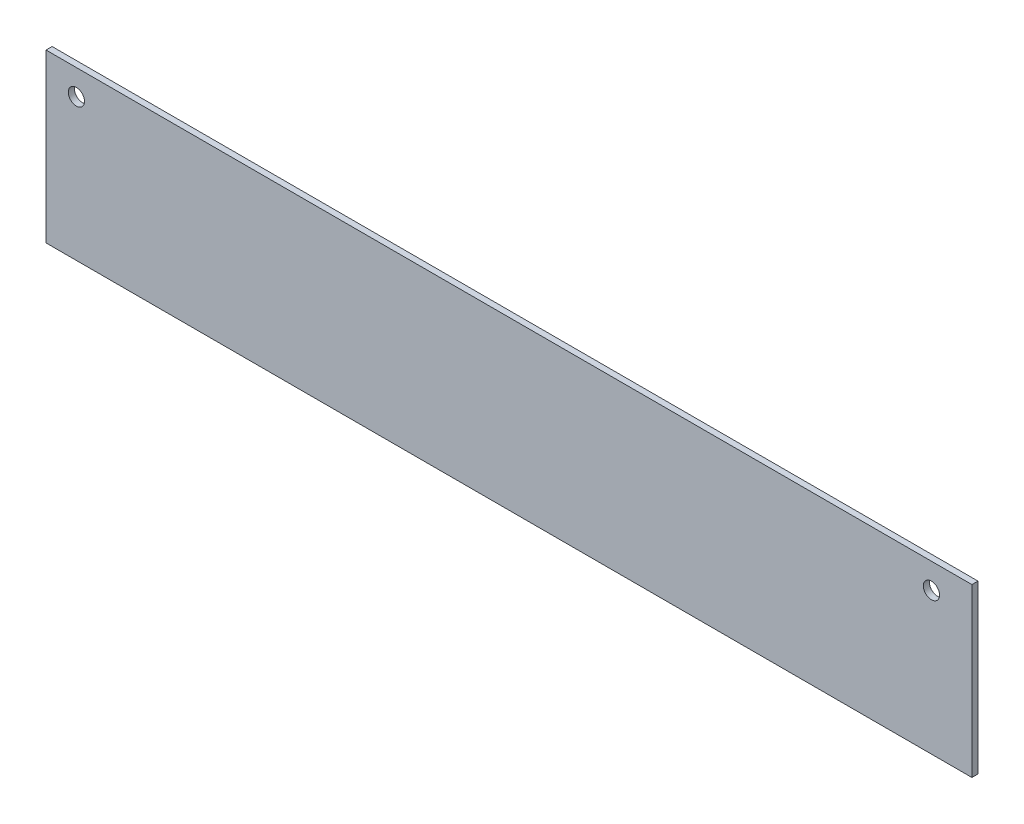
SolidWorks part; units mm, degrees
ref_plane "Front Plane" through (0, 0, 0) normal (0, 0, 1) x (1, 0, 0)
ref_plane "Top Plane" through (0, 0, 0) normal (0, 1, 0) x (1, 0, 0)
ref_plane "Right Plane" through (0, 0, 0) normal (1, 0, 0) x (0, 0, -1)
sketch "Sketch1" plane through (0, 0, 0) normal (0, 0, 1) x (1, 0, 0)
  line L1 (-228.6, 41.25) -> (228.6, 41.25)
  line L2 (-228.6, 41.25) -> (-228.6, -41.25)
  line L3 (-228.6, -41.25) -> (228.6, -41.25)
  line L4 (228.6, 41.25) -> (228.6, -41.25)
  line L5 (-228.6, 41.25) -> (228.6, -41.25) construction
  line L6 (-228.6, -41.25) -> (228.6, 41.25) construction
  point P0 (0, 0)
  dimension "D1" = 457.2
  dimension "D2" = 82.5
extrude "Boss-Extrude1" add sketch "Sketch1" along normal blind 3
sketch "Sketch2" plane through (0, 0, 3) normal (0, 0, 1) x (1, 0, 0)
  line L0 (-228.6, 41.25) -> (-228.6, -41.25) construction
  line L2 (228.6, -41.25) -> (228.6, 41.25) construction
  line L3 (228.6, 41.25) -> (-228.6, 41.25) construction
  circle A0 centre (-213.6, 28.75) radius 4
  circle A1 centre (208.6, 28.75) radius 4
  dimension "D1" = 8
  dimension "D3" = 8
  dimension "D2" = 15
  dimension "D4" = 20
  dimension "D5" = 12.5
  dimension "D6" = 12.5
extrude "Cut-Extrude1" cut sketch "Sketch2" against normal through all
